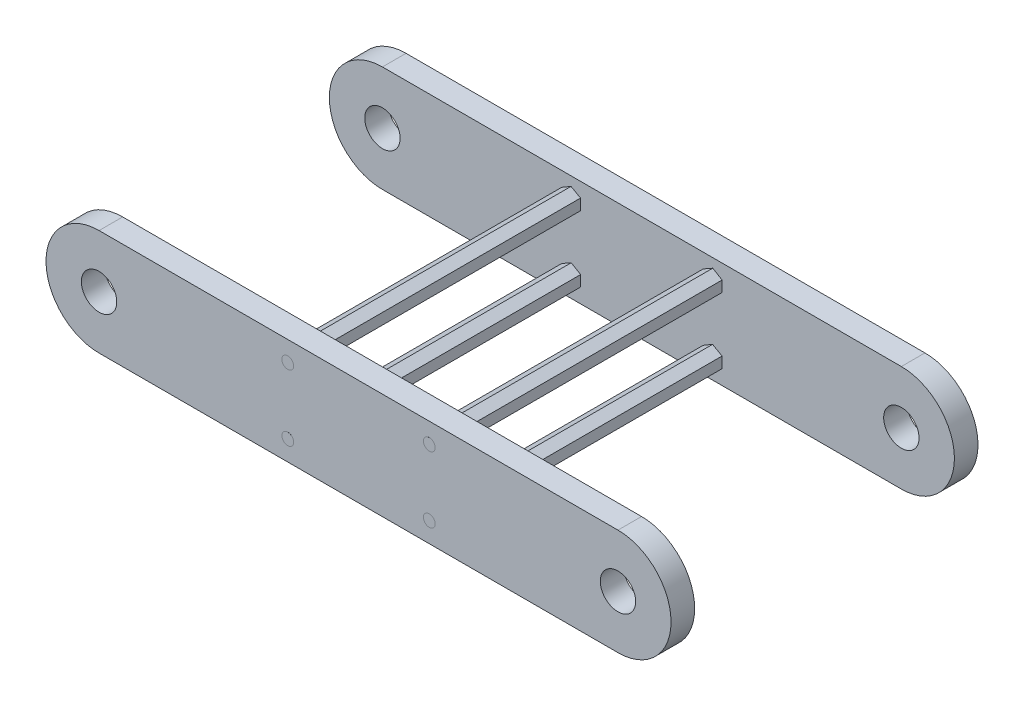
SolidWorks part; units mm, degrees
ref_plane "Front Plane" through (0, 0, 0) normal (0, 0, 1) x (1, 0, 0)
ref_plane "Top Plane" through (0, 0, 0) normal (0, 1, 0) x (1, 0, 0)
ref_plane "Right Plane" through (0, 0, 0) normal (1, 0, 0) x (0, 0, -1)
sketch "Sketch1" plane through (0, 0, 0) normal (0, 0, 1) x (1, 0, 0)
  line L0 (-45, 22.5) -> (-265, 22.5)
  line L1 (-45, -22.5) -> (-265, -22.5)
  line L2 (-265, 0) -> (-45, 0) construction
  circle A0 centre (-45, 0) radius 7.5
  arc A1 (-45, -22.5) -> (-45, 22.5) centre (-45, 0) ccw
  arc A2 (-265, -22.5) -> (-265, 22.5) centre (-265, 0) cw
  circle A3 centre (-265, 0) radius 7.5
  dimension "D1" = 22.5
  dimension "D2" = 15
  dimension "D3" = 15
  dimension "D4" = 22.5
  dimension "D5" = 220
extrude "Boss-Extrude1" add sketch "Sketch1" along normal blind 10
ref_plane "Plane1" through (0, 0, -55.07) normal (0, 0, -1) x (-1, 0, 0)
sketch "Sketch2" plane through (0, 0, 10) normal (0, 0, 1) x (1, 0, 0)
  line L0 (-155, 22.5) -> (-155, -29.0102) construction
  line L1 (-45, 22.5) -> (-265, 22.5) construction
  line L2 (-265, 0) -> (-245.2122, 0) construction
  circle A0 centre (-185, 14) radius 2.5
  circle A1 centre (-125, 14) radius 2.5
  circle A2 centre (-185, -14) radius 2.5
  circle A3 centre (-125, -14) radius 2.5
  dimension "D1" = 5
  dimension "D3" = 60
  dimension "D2" = 28
extrude "Cut-Extrude1" cut sketch "Sketch2" against normal blind 10
sketch "Sketch4" plane through (0, 0, 0) normal (0, 0, -1) x (-1, 0, 0)
  line L0 (155, 22.5) -> (155, -22.5) construction
  line L1 (129.0192, 11.7242) -> (128.9805, 16.3428)
  line L2 (128.9805, 16.3428) -> (124.9613, 18.6186)
  line L3 (124.9613, 18.6186) -> (120.9808, 16.2758)
  line L4 (120.9808, 16.2758) -> (121.0195, 11.6572)
  line L5 (121.0195, 11.6572) -> (125.0387, 9.3814)
  line L6 (125.0387, 9.3814) -> (129.0192, 11.7242)
  line L7 (45, 22.5) -> (265, 22.5) construction
  line L8 (265, -22.5) -> (45, -22.5) construction
  line L9 (184.9613, 9.3814) -> (180.9808, 11.7242)
  line L10 (22.5, 0) -> (287.5, 0) construction
  line L11 (188.9805, 11.6572) -> (184.9613, 9.3814)
  line L12 (189.0192, 16.2758) -> (188.9805, 11.6572)
  line L13 (185.0387, 18.6186) -> (189.0192, 16.2758)
  line L14 (181.0195, 16.3428) -> (185.0387, 18.6186)
  line L15 (180.9808, 11.7242) -> (181.0195, 16.3428)
  line L16 (121.0195, -11.6572) -> (125.0387, -9.3814)
  line L17 (120.9808, -16.2758) -> (121.0195, -11.6572)
  line L18 (125.0387, -9.3814) -> (129.0192, -11.7242)
  line L19 (124.9613, -18.6186) -> (120.9808, -16.2758)
  line L20 (128.9805, -16.3428) -> (124.9613, -18.6186)
  line L21 (129.0192, -11.7242) -> (128.9805, -16.3428)
  line L22 (180.9808, -11.7242) -> (181.0195, -16.3428)
  line L23 (181.0195, -16.3428) -> (185.0387, -18.6186)
  line L24 (185.0387, -18.6186) -> (189.0192, -16.2758)
  line L25 (189.0192, -16.2758) -> (188.9805, -11.6572)
  line L26 (188.9805, -11.6572) -> (184.9613, -9.3814)
  line L27 (184.9613, -9.3814) -> (180.9808, -11.7242)
  circle A0 centre (125, 14) radius 4 construction
  arc A1 (45, 22.5) -> (45, -22.5) centre (45, 0) ccw construction
  arc A2 (265, -22.5) -> (265, 22.5) centre (265, 0) ccw construction
  circle A3 centre (185, 14) radius 4 construction
  circle A4 centre (125, -14) radius 4 construction
  circle A5 centre (185, -14) radius 4 construction
  dimension "D1" = 8
extrude "Boss-Extrude3" add sketch "Sketch4" along normal blind 120.14
sketch "Sketch5" plane through (0, 0, 0) normal (0, 0, 1) x (1, 0, 0)
  circle A0 centre (-185, 14) radius 2.5 construction
  circle A1 centre (-125, 14) radius 2.5
  circle A2 centre (-125, 14) radius 2.5
  circle A3 centre (-185, 14) radius 2.5
  circle A4 centre (-125, -14) radius 2.5 construction
  circle A5 centre (-125, -14) radius 2.5
  circle A6 centre (-185, -14) radius 2.5 construction
  circle A7 centre (-185, -14) radius 2.5
  dimension "D1" = 0
extrude "Boss-Extrude4" add sketch "Sketch5" along normal up to surface (10 mm away) separate body up to face at (-127.5, 14, 10)
mirror "Mirror6" about plane through (0, 0, -55.07) normal (0, 0, -1) of "Boss-Extrude1", "Cut-Extrude1"
sketch "Sketch6" plane through (0, 0, -110.14) normal (0, 0, -1) x (-1, 0, 0)
  circle A1 centre (185, -14) radius 2.5 construction
  circle A8 centre (185, 14) radius 2.5 construction
  circle A9 centre (125, 14) radius 2.5 construction
  circle A10 centre (125, -14) radius 2.5 construction
  circle A11 centre (185, -14) radius 2.5
  circle A12 centre (185, 14) radius 2.5
  circle A13 centre (125, 14) radius 2.5
  circle A14 centre (125, -14) radius 2.5
extrude "Boss-Extrude6" add sketch "Sketch6" along normal up to surface (10 mm away) separate body contours A11 | A12 | A13 | A14 up to face at (-127.5, 14, -120.14)
